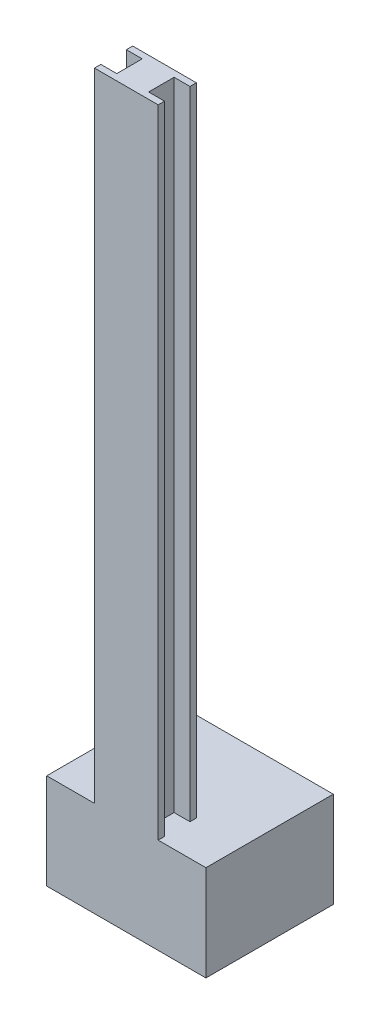
SolidWorks part; units mm, degrees
ref_plane "Front Plane" through (0, 0, 0) normal (0, 0, 1) x (1, 0, 0)
ref_plane "Top Plane" through (0, 0, 0) normal (0, 1, 0) x (1, 0, 0)
ref_plane "Right Plane" through (0, 0, 0) normal (1, 0, 0) x (0, 0, -1)
sketch "Esquisse1" plane through (0, 0, 0) normal (0, 1, 0) x (1, 0, 0)
  line L1 (-25, -20) -> (25, -20)
  line L2 (-25, -20) -> (-25, 20)
  line L3 (-25, 20) -> (25, 20)
  line L4 (25, -20) -> (25, 20)
  line L5 (-25, -20) -> (25, 20) construction
  line L6 (-25, 20) -> (25, -20) construction
  point P0 (0, 0)
  dimension "D1" = 40
  dimension "D2" = 50
extrude "Boss.-Extru.1" add sketch "Esquisse1" along normal blind 30
sketch "Esquisse2" plane through (0, 30, 0) normal (0, 1, 0) x (1, 0, 0)
  line L0 (-25, -20) -> (25, -20) construction
  line L1 (-10, -20) -> (10, -20)
  line L2 (-10, -20) -> (-10, -18)
  line L3 (-10, -8) -> (10, -8)
  line L4 (10, -20) -> (10, -18)
  line L5 (-10, -10) -> (-5, -10)
  line L6 (-5, -10) -> (-5, -18)
  line L7 (-5, -18) -> (-10, -18)
  line L8 (10, -10) -> (5, -10)
  line L9 (5, -10) -> (5, -18)
  line L10 (5, -18) -> (10, -18)
  line L11 (-10, -10) -> (-10, -8)
  line L12 (10, -10) -> (10, -8)
  dimension "D1" = 12
  dimension "D2" = 20
  dimension "D3" = 10
  dimension "D4" = 8
  dimension "D5" = 2
  dimension "D6" = 5
  dimension "D7" = 5
extrude "Boss.-Extru.2" add sketch "Esquisse2" along normal blind 200
